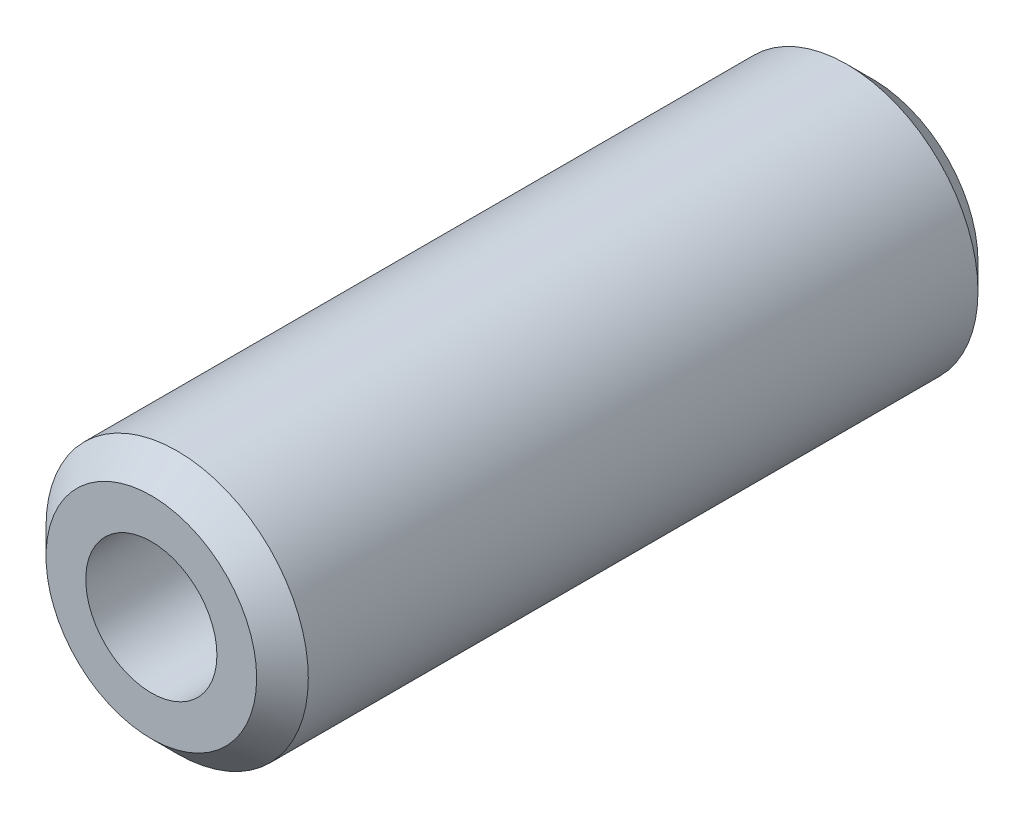
SolidWorks part; units mm, degrees
ref_plane "Front Plane" through (0, 0, 0) normal (0, 0, 1) x (1, 0, 0)
ref_plane "Top Plane" through (0, 0, 0) normal (0, 1, 0) x (1, 0, 0)
ref_plane "Right Plane" through (0, 0, 0) normal (1, 0, 0) x (0, 0, -1)
sketch "Sketch1" plane through (0, 0, 0) normal (0, 0, 1) x (1, 0, 0)
  circle A0 centre (0, 0) radius 12.7
  circle A1 centre (0, 0) radius 6.35
  dimension "D1" = 12.7
  dimension "D2" = 25.4
extrude "Boss-Extrude1" add sketch "Sketch1" along normal blind 69.85
chamfer "Chamfer1" distance 2.5 angle 45 1 edges at (12.7, 0, 69.85)
chamfer "Chamfer2" distance 2.5 angle 45 1 edges at (12.7, 0, 0)
